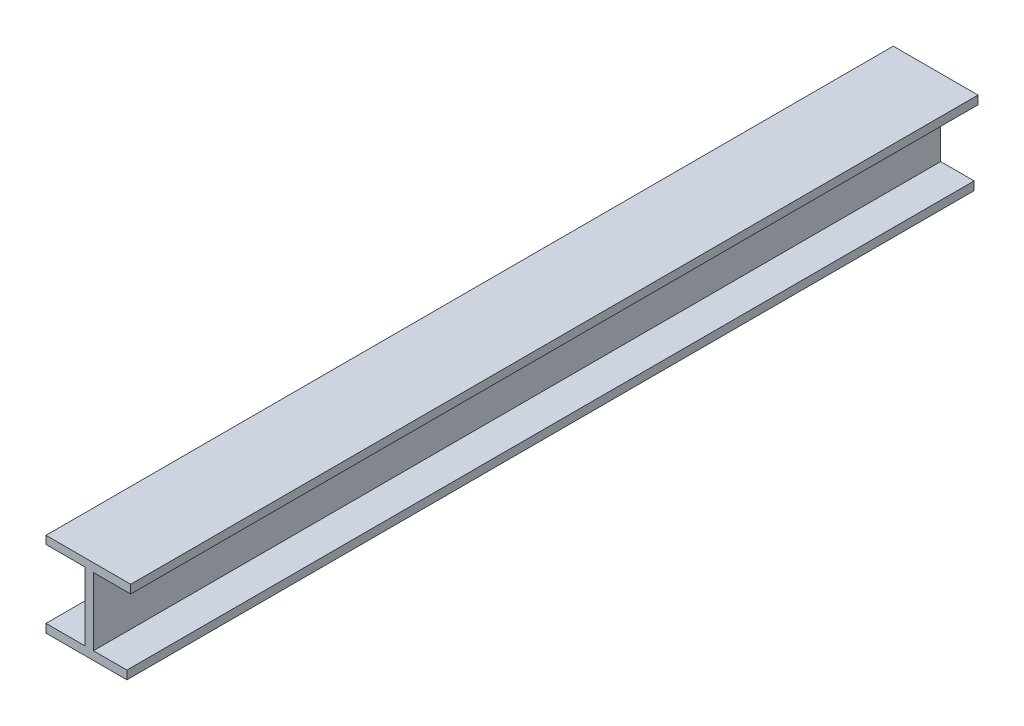
SolidWorks part; units mm, degrees
ref_plane "Front Plane" through (0, 0, 0) normal (0, 0, 1) x (1, 0, 0)
ref_plane "Top Plane" through (0, 0, 0) normal (0, 1, 0) x (1, 0, 0)
ref_plane "Right Plane" through (0, 0, 0) normal (1, 0, 0) x (0, 0, -1)
sketch "Sketch1" plane through (0, 0, 0) normal (0, 0, 1) x (1, 0, 0)
  line L0 (-45.9547, 67.4757) -> (-45.9547, 58.0906)
  line L1 (-45.9547, 58.0906) -> (0, 58.0906)
  line L2 (0, 58.0906) -> (0, -22.5243)
  line L3 (0, -22.5243) -> (-45.9547, -22.5243)
  line L4 (-45.9547, -22.5243) -> (-45.9547, -32.5243)
  line L5 (-45.9547, -32.5243) -> (49.5146, -32.5243)
  line L6 (49.5146, -32.5243) -> (49.5146, -22.5243)
  line L7 (49.5146, -22.5243) -> (10, -22.5243)
  line L8 (10, -22.5243) -> (10, 57.4757)
  line L9 (10, 57.4757) -> (54.0453, 57.4757)
  line L10 (54.0453, 57.4757) -> (54.0453, 67.4757)
  line L11 (54.0453, 67.4757) -> (-45.9547, 67.4757)
  dimension "D1" = 100
  dimension "D2" = 10
  dimension "D3" = 10
  dimension "D4" = 100
  dimension "D5" = 10
extrude "Boss-Extrude1" add sketch "Sketch1" along normal blind 1000
